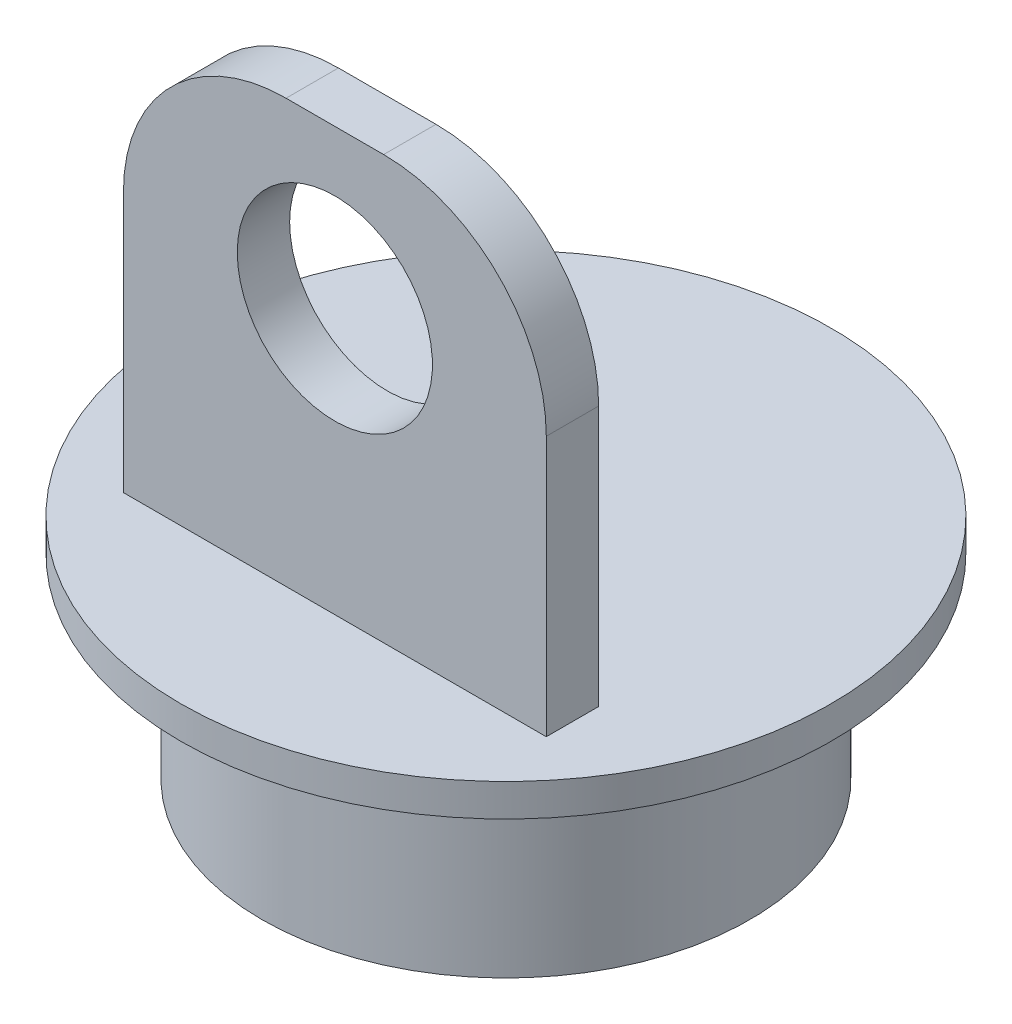
SolidWorks part; units mm, degrees
material "6063-T6"
ref_plane "Front Plane" through (0, 0, 0) normal (0, 0, 1) x (1, 0, 0)
ref_plane "Top Plane" through (0, 0, 0) normal (0, 1, 0) x (1, 0, 0)
ref_plane "Right Plane" through (0, 0, 0) normal (1, 0, 0) x (0, 0, -1)
sketch "Sketch3" plane through (0, 0, 0) normal (0, 1, 0) x (1, 0, 0)
  circle A0 centre (0, 0) radius 37.5
  circle A1 centre (0, 0) radius 32.5
  dimension "D1" = 75
  dimension "D2" = 65
extrude "Boss-Extrude1" add sketch "Sketch3" along normal blind 30
sketch "Sketch4" plane through (0, 30, 0) normal (0, 1, 0) x (1, 0, 0)
  circle A0 centre (0, 0) radius 50
extrude "Boss-Extrude2" add sketch "Sketch4" along normal blind 5
sketch "Sketch5" plane through (0, 35, 0) normal (0, 1, 0) x (1, 0, 0)
  line L1 (-32.5, -18.2448) -> (32.5, -18.2448)
  line L2 (-32.5, -18.2448) -> (-32.5, -26.294)
  line L3 (-32.5, -26.294) -> (32.5, -26.294)
  line L4 (32.5, -18.2448) -> (32.5, -26.294)
  point P4 (0, -18.2448)
  dimension "D1" = 65
  dimension "D2" = 0
extrude "Boss-Extrude3" add sketch "Sketch5" along normal blind 65
fillet "Fillet1" radius 25 2 edges at (-32.5, 100, 22.2694) (32.5, 100, 22.2694)
sketch "Sketch6" plane through (0, 0, 18.2448) normal (0, 0, -1) x (-1, 0, 0)
  circle A0 centre (0, 75.7573) radius 15
  dimension "D1" = 30
extrude "Cut-Extrude1" cut sketch "Sketch6" against normal blind 10
